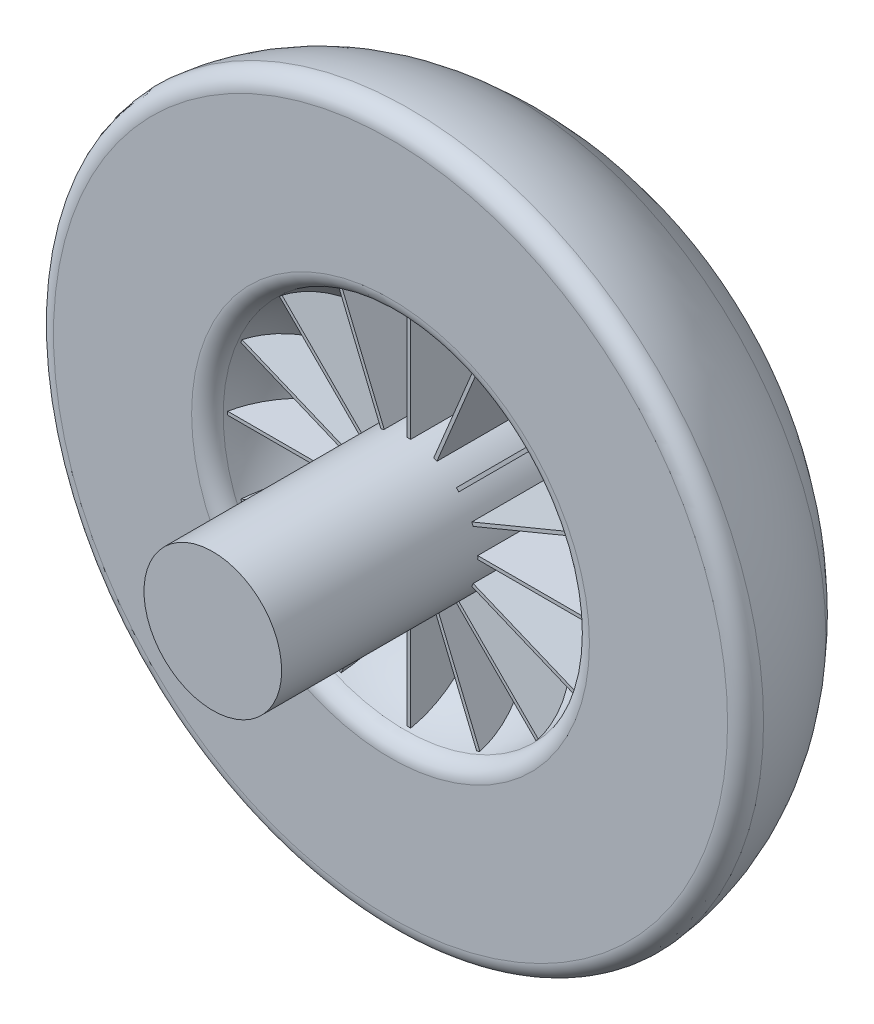
SolidWorks part; units mm, degrees
ref_plane "Front Plane" through (0, 0, 0) normal (0, 0, 1) x (1, 0, 0)
ref_plane "Top Plane" through (0, 0, 0) normal (0, 1, 0) x (1, 0, 0)
ref_plane "Right Plane" through (0, 0, 0) normal (1, 0, 0) x (0, 0, -1)
sketch "Sketch1" plane through (0, 0, 0) normal (0, 1, 0) x (1, 0, 0)
  line L0 (0, -1001.2658) -> (0, 49062.0266) construction
  line L1 (0, 40) -> (24, 40)
  line L2 (103.2055, -27.3476) -> (53.2055, -27.3476)
  line L3 (20, 0) -> (27.5, 0)
  line L4 (0, 0) -> (0, 40)
  line L7 (0, 0) -> (0, -79)
  line L8 (0, -79) -> (20, -79)
  line L9 (20, 0) -> (20, -79)
  arc A0 (24, 40) -> (89.8509, 9.3141) centre (24, -46) cw
  arc A1 (89.8509, 9.3141) -> (103.2055, -27.3476) centre (46.2055, -27.3476) cw
  arc A2 (53.2055, -27.3476) -> (27.5, 0) centre (25.8055, -27.3476) ccw
  point P16 (20, -0.5325)
  point P17 (0, 0)
  dimension "D2" = 27.4
  dimension "D3" = 86
  dimension "D4" = 57
  dimension "D1" = 50
  dimension "D5" = 40
  dimension "D6" = 24
  dimension "D7" = 27.5
  dimension "D8" = 79
  dimension "D9" = 20
revolve "Revolve1" add sketch "Sketch1" angle 360 about L0
fillet "Fillet1" radius 5 2 edges at (53.2055, 0, 27.3476) (103.2055, 0, 27.3476)
sketch "Sketch2" plane through (0, 0, 0) normal (1, 0, 0) x (0, 0, -1)
  line L1 (0, 0) -> (-22, 0)
  line L2 (0, 0) -> (0, -65)
  line L3 (0, -65) -> (-22, -65)
  line L4 (-22, 0) -> (-22, -65)
  point P5 (-21.7452, -67.3795)
  dimension "D1" = 22
  dimension "D2" = 65
extrude "Boss-Extrude1" add sketch "Sketch2" along normal mid plane 1
pattern_circular "CirPattern1" count 16 over 360 about axis through (0, 0, 0) along (0, 0, 1) of "Boss-Extrude1"
